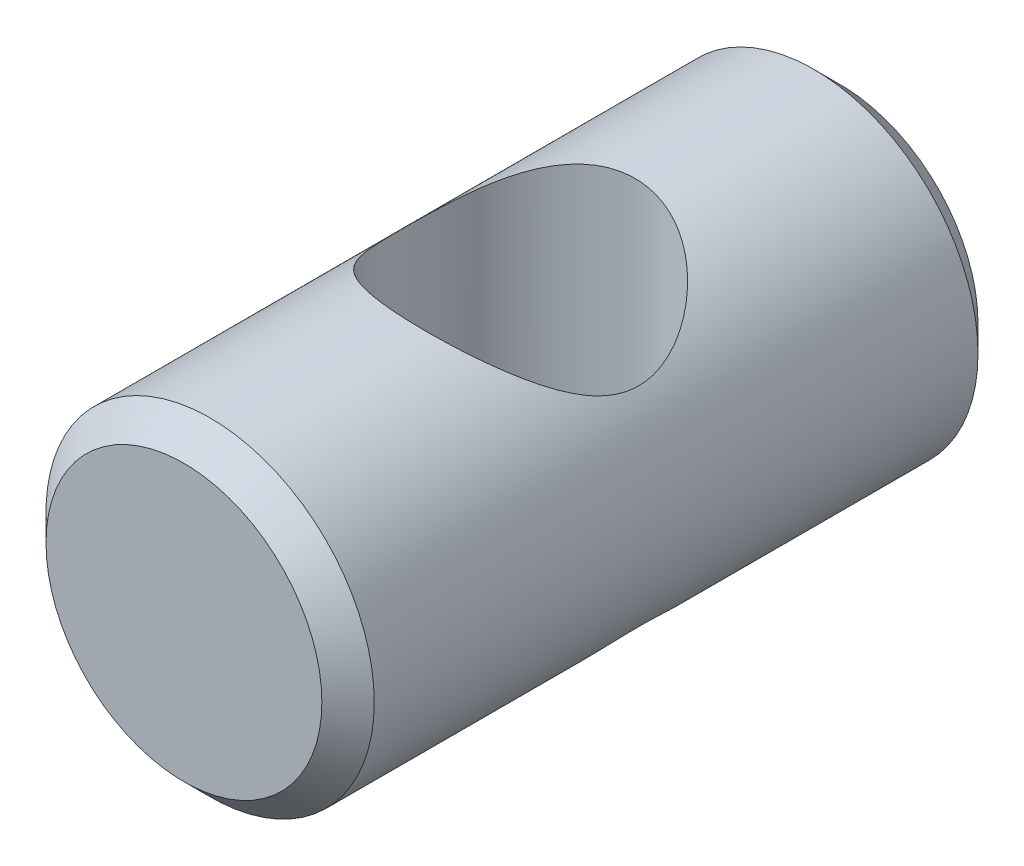
SolidWorks part; units mm, degrees
ref_plane "Front Plane" through (0, 0, 0) normal (0, 0, 1) x (1, 0, 0)
ref_plane "Top Plane" through (0, 0, 0) normal (0, 1, 0) x (1, 0, 0)
ref_plane "Right Plane" through (0, 0, 0) normal (1, 0, 0) x (0, 0, -1)
sketch "Sketch1" plane through (0, 0, 0) normal (0, 0, 1) x (1, 0, 0)
  circle A0 centre (0, 0) radius 4.765
  dimension "D1" = 9.53
extrude "Boss-Extrude1" add sketch "Sketch1" along normal mid plane 19.05
chamfer "Chamfer1" distance 0.76 angle 45 2 edges at (4.765, 0, -9.525) (4.765, 0, 9.525)
sketch "Sketch2" plane through (0, 0, 0) normal (0, 1, 0) x (1, 0, 0)
  circle A0 centre (0.25, 0) radius 3.43
  point P5 (0, 0)
  dimension "D1" = 6.86
  dimension "D2" = 0.25
extrude "Cut-Extrude1" cut sketch "Sketch2" against normal through all both and the other way through all
